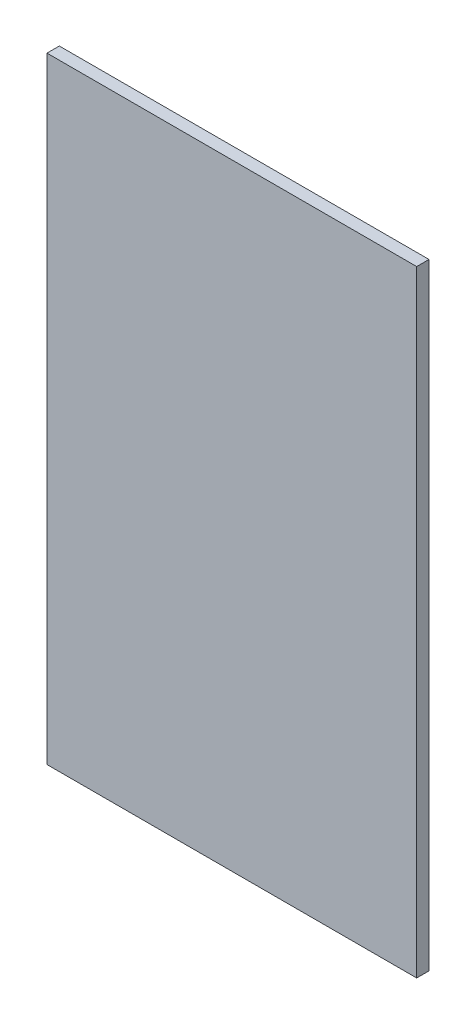
SolidWorks part; units mm, degrees
ref_plane "Front Plane" through (0, 0, 0) normal (0, 0, 1) x (1, 0, 0)
ref_plane "Top Plane" through (0, 0, 0) normal (0, 1, 0) x (1, 0, 0)
ref_plane "Right Plane" through (0, 0, 0) normal (1, 0, 0) x (0, 0, -1)
sketch "Sketch1" plane through (0, 0, 0) normal (0, 0, 1) x (1, 0, 0)
  line L1 (0, 0) -> (90, 0)
  line L2 (0, 0) -> (0, 150)
  line L3 (0, 150) -> (90, 150)
  line L4 (90, 0) -> (90, 150)
  dimension "D1" = 90
  dimension "D2" = 150
extrude "Boss-Extrude1" add sketch "Sketch1" along normal blind 3
